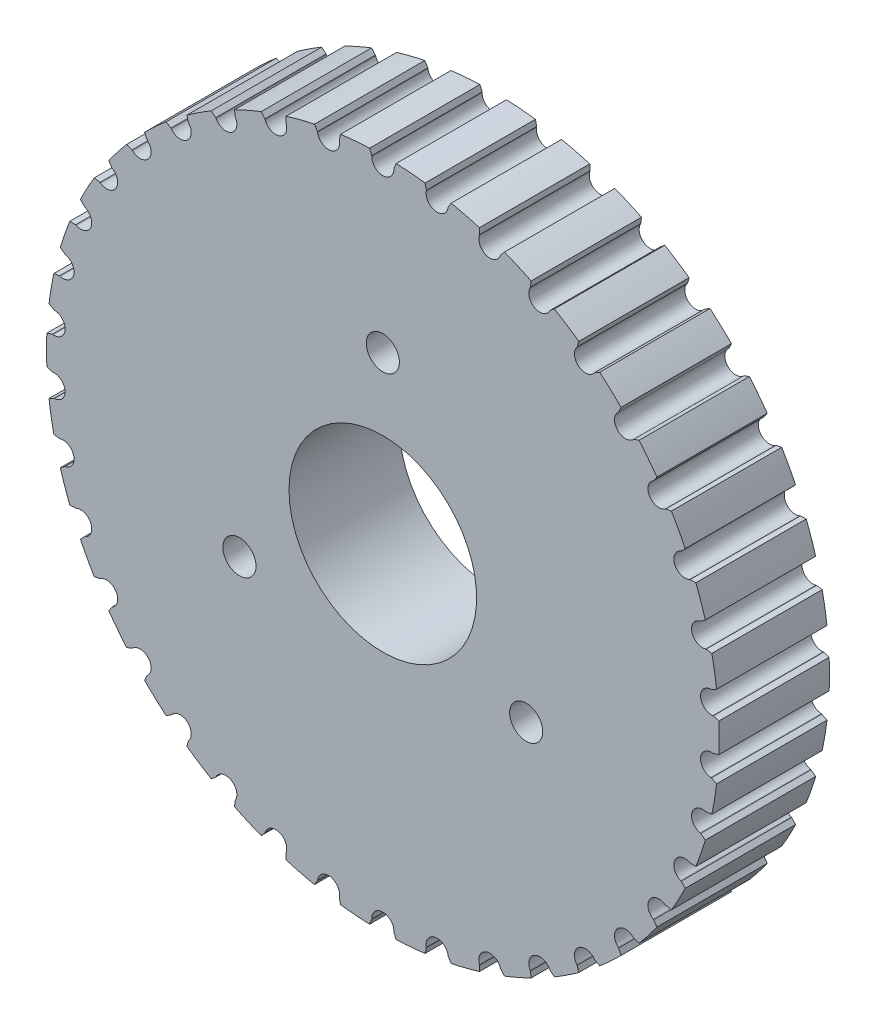
SolidWorks part; units mm, degrees
ref_plane "Спереди" through (0, 0, 0) normal (0, 0, 1) x (1, 0, 0)
ref_plane "Сверху" through (0, 0, 0) normal (0, 1, 0) x (1, 0, 0)
ref_plane "Справа" through (0, 0, 0) normal (1, 0, 0) x (0, 0, -1)
sketch "Эскиз1" plane through (0, 0, 0) normal (0, 0, 1) x (1, 0, 0)
  line L0 (0, 0) -> (0, 54.1155) construction
  line L1 (-1.2, 30.4464) -> (-1, 29.9592)
  line L2 (3.8277, 30.2286) -> (3.9448, 29.7152)
  line L3 (1, 29.9592) -> (1.2, 30.4464)
  line L4 (0, 30.47) -> (13.54, 30.47) construction
  line L5 (1, 29.9592) -> (1, 29.8903)
  line L6 (5.9175, 29.386) -> (6.1949, 29.8336)
  line L7 (-1, 29.9592) -> (-1, 29.8903)
  line L8 (5.9175, 29.386) -> (5.9061, 29.3181)
  line L9 (3.9448, 29.7152) -> (3.9334, 29.6473)
  line L10 (8.7509, 29.1863) -> (8.7819, 28.6606)
  line L11 (10.6736, 28.0112) -> (11.0209, 28.4071)
  line L12 (10.6736, 28.0112) -> (10.6512, 27.9461)
  line L13 (8.7819, 28.6606) -> (8.7596, 28.5955)
  line L14 (13.4355, 27.3479) -> (13.3795, 26.8243)
  line L15 (15.1385, 25.8724) -> (15.5462, 26.2056)
  line L16 (15.1385, 25.8724) -> (15.1057, 25.8118)
  line L17 (13.3795, 26.8243) -> (13.3468, 26.7637)
  line L18 (17.7536, 24.7635) -> (17.6122, 24.2562)
  line L19 (19.1905, 23.0278) -> (19.6475, 23.2894)
  line L20 (19.1905, 23.0278) -> (19.1482, 22.9735)
  line L21 (17.6122, 24.2562) -> (17.5699, 24.2019)
  line L22 (21.5874, 21.5036) -> (21.3644, 21.0265)
  line L23 (22.719, 19.5551) -> (23.2129, 19.7379)
  line L24 (22.719, 19.5551) -> (22.6683, 19.5085)
  line L25 (21.3644, 21.0265) -> (21.3138, 20.9799)
  line L26 (24.8323, 17.6572) -> (24.5339, 17.2233)
  line L27 (25.6278, 15.549) -> (26.145, 15.648)
  line L28 (25.6278, 15.549) -> (25.5701, 15.5113)
  line L29 (24.5339, 17.2233) -> (24.4762, 17.1856)
  line L30 (27.3999, 13.3291) -> (27.0341, 12.9502)
  line L31 (27.8375, 11.1187) -> (28.364, 11.1312)
  line L32 (27.8375, 11.1187) -> (27.7745, 11.091)
  line L33 (27.0341, 12.9502) -> (26.9711, 12.9226)
  line L34 (29.2201, 8.6374) -> (28.797, 8.3239)
  line L35 (29.2879, 6.3851) -> (29.8093, 6.3109)
  line L36 (29.2879, 6.3851) -> (29.2212, 6.3682)
  line L37 (28.797, 8.3239) -> (28.7302, 8.307)
  line L38 (30.2433, 3.7101) -> (29.7743, 3.4706)
  line L39 (29.9395, 1.4774) -> (30.4415, 1.3183)
  line L40 (29.9395, 1.4774) -> (29.8708, 1.4717)
  line L41 (29.7743, 3.4706) -> (29.7057, 3.4649)
  line L42 (30.4415, -1.3183) -> (29.9395, -1.4774)
  line L43 (29.7743, -3.4706) -> (30.2433, -3.7101)
  line L44 (29.7743, -3.4706) -> (29.7057, -3.4649)
  line L45 (29.9395, -1.4774) -> (29.8708, -1.4717)
  line L46 (29.8093, -6.3109) -> (29.2879, -6.3851)
  line L47 (28.797, -8.3239) -> (29.2201, -8.6374)
  line L48 (28.797, -8.3239) -> (28.7302, -8.307)
  line L49 (29.2879, -6.3851) -> (29.2212, -6.3682)
  line L50 (28.364, -11.1312) -> (27.8375, -11.1187)
  line L51 (27.0341, -12.9502) -> (27.3999, -13.3291)
  line L52 (27.0341, -12.9502) -> (26.9711, -12.9226)
  line L53 (27.8375, -11.1187) -> (27.7745, -11.091)
  line L54 (26.145, -15.648) -> (25.6278, -15.549)
  line L55 (24.5339, -17.2233) -> (24.8323, -17.6572)
  line L56 (24.5339, -17.2233) -> (24.4762, -17.1856)
  line L57 (25.6278, -15.549) -> (25.5701, -15.5113)
  line L58 (23.2129, -19.7379) -> (22.719, -19.5551)
  line L59 (21.3644, -21.0265) -> (21.5874, -21.5036)
  line L60 (21.3644, -21.0265) -> (21.3138, -20.9799)
  line L61 (22.719, -19.5551) -> (22.6683, -19.5085)
  line L62 (19.6475, -23.2894) -> (19.1905, -23.0278)
  line L63 (17.6122, -24.2562) -> (17.7536, -24.7635)
  line L64 (17.6122, -24.2562) -> (17.5699, -24.2019)
  line L65 (19.1905, -23.0278) -> (19.1482, -22.9735)
  line L66 (15.5462, -26.2056) -> (15.1385, -25.8724)
  line L67 (13.3795, -26.8243) -> (13.4355, -27.3479)
  line L68 (13.3795, -26.8243) -> (13.3468, -26.7637)
  line L69 (15.1385, -25.8724) -> (15.1057, -25.8118)
  line L70 (11.0209, -28.4071) -> (10.6736, -28.0112)
  line L71 (8.7819, -28.6606) -> (8.7509, -29.1863)
  line L72 (8.7819, -28.6606) -> (8.7596, -28.5955)
  line L73 (10.6736, -28.0112) -> (10.6512, -27.9461)
  line L74 (6.1949, -29.8336) -> (5.9175, -29.386)
  line L75 (3.9448, -29.7152) -> (3.8277, -30.2286)
  line L76 (3.9448, -29.7152) -> (3.9334, -29.6473)
  line L77 (5.9175, -29.386) -> (5.9061, -29.3181)
  line L78 (1.2, -30.4464) -> (1, -29.9592)
  line L79 (-1, -29.9592) -> (-1.2, -30.4464)
  line L80 (-1, -29.9592) -> (-1, -29.8903)
  line L81 (1, -29.9592) -> (1, -29.8903)
  line L82 (-3.8277, -30.2286) -> (-3.9448, -29.7152)
  line L83 (-5.9175, -29.386) -> (-6.1949, -29.8336)
  line L84 (-5.9175, -29.386) -> (-5.9061, -29.3181)
  line L85 (-3.9448, -29.7152) -> (-3.9334, -29.6473)
  line L86 (-8.7509, -29.1863) -> (-8.7819, -28.6606)
  line L87 (-10.6736, -28.0112) -> (-11.0209, -28.4071)
  line L88 (-10.6736, -28.0112) -> (-10.6512, -27.9461)
  line L89 (-8.7819, -28.6606) -> (-8.7596, -28.5955)
  line L90 (-13.4355, -27.3479) -> (-13.3795, -26.8243)
  line L91 (-15.1385, -25.8724) -> (-15.5462, -26.2056)
  line L92 (-15.1385, -25.8724) -> (-15.1057, -25.8118)
  line L93 (-13.3795, -26.8243) -> (-13.3468, -26.7637)
  line L94 (-17.7536, -24.7635) -> (-17.6122, -24.2562)
  line L95 (-19.1905, -23.0278) -> (-19.6475, -23.2894)
  line L96 (-19.1905, -23.0278) -> (-19.1482, -22.9735)
  line L97 (-17.6122, -24.2562) -> (-17.5699, -24.2019)
  line L98 (-21.5874, -21.5036) -> (-21.3644, -21.0265)
  line L99 (-22.719, -19.5551) -> (-23.2129, -19.7379)
  line L100 (-22.719, -19.5551) -> (-22.6683, -19.5085)
  line L101 (-21.3644, -21.0265) -> (-21.3138, -20.9799)
  line L102 (-24.8323, -17.6572) -> (-24.5339, -17.2233)
  line L103 (-25.6278, -15.549) -> (-26.145, -15.648)
  line L104 (-25.6278, -15.549) -> (-25.5701, -15.5113)
  line L105 (-24.5339, -17.2233) -> (-24.4762, -17.1856)
  line L106 (-27.3999, -13.3291) -> (-27.0341, -12.9502)
  line L107 (-27.8375, -11.1187) -> (-28.364, -11.1312)
  line L108 (-27.8375, -11.1187) -> (-27.7745, -11.091)
  line L109 (-27.0341, -12.9502) -> (-26.9711, -12.9226)
  line L110 (-29.2201, -8.6374) -> (-28.797, -8.3239)
  line L111 (-29.2879, -6.3851) -> (-29.8093, -6.3109)
  line L112 (-29.2879, -6.3851) -> (-29.2212, -6.3682)
  line L113 (-28.797, -8.3239) -> (-28.7302, -8.307)
  line L114 (-30.2433, -3.7101) -> (-29.7743, -3.4706)
  line L115 (-29.9395, -1.4774) -> (-30.4415, -1.3183)
  line L116 (-29.9395, -1.4774) -> (-29.8708, -1.4717)
  line L117 (-29.7743, -3.4706) -> (-29.7057, -3.4649)
  line L118 (-30.4415, 1.3183) -> (-29.9395, 1.4774)
  line L119 (-29.7743, 3.4706) -> (-30.2433, 3.7101)
  line L120 (-29.7743, 3.4706) -> (-29.7057, 3.4649)
  line L121 (-29.9395, 1.4774) -> (-29.8708, 1.4717)
  line L122 (-29.8093, 6.3109) -> (-29.2879, 6.3851)
  line L123 (-28.797, 8.3239) -> (-29.2201, 8.6374)
  line L124 (-28.797, 8.3239) -> (-28.7302, 8.307)
  line L125 (-29.2879, 6.3851) -> (-29.2212, 6.3682)
  line L126 (-28.364, 11.1312) -> (-27.8375, 11.1187)
  line L127 (-27.0341, 12.9502) -> (-27.3999, 13.3291)
  line L128 (-27.0341, 12.9502) -> (-26.9711, 12.9226)
  line L129 (-27.8375, 11.1187) -> (-27.7745, 11.091)
  line L130 (-26.145, 15.648) -> (-25.6278, 15.549)
  line L131 (-24.5339, 17.2233) -> (-24.8323, 17.6572)
  line L132 (-24.5339, 17.2233) -> (-24.4762, 17.1856)
  line L133 (-25.6278, 15.549) -> (-25.5701, 15.5113)
  line L134 (-23.2129, 19.7379) -> (-22.719, 19.5551)
  line L135 (-21.3644, 21.0265) -> (-21.5874, 21.5036)
  line L136 (-21.3644, 21.0265) -> (-21.3138, 20.9799)
  line L137 (-22.719, 19.5551) -> (-22.6683, 19.5085)
  line L138 (-19.6475, 23.2894) -> (-19.1905, 23.0278)
  line L139 (-17.6122, 24.2562) -> (-17.7536, 24.7635)
  line L140 (-17.6122, 24.2562) -> (-17.5699, 24.2019)
  line L141 (-19.1905, 23.0278) -> (-19.1482, 22.9735)
  line L142 (-15.5462, 26.2056) -> (-15.1385, 25.8724)
  line L143 (-13.3795, 26.8243) -> (-13.4355, 27.3479)
  line L144 (-13.3795, 26.8243) -> (-13.3468, 26.7637)
  line L145 (-15.1385, 25.8724) -> (-15.1057, 25.8118)
  line L146 (-11.0209, 28.4071) -> (-10.6736, 28.0112)
  line L147 (-8.7819, 28.6606) -> (-8.7509, 29.1863)
  line L148 (-8.7819, 28.6606) -> (-8.7596, 28.5955)
  line L149 (-10.6736, 28.0112) -> (-10.6512, 27.9461)
  line L150 (-6.1949, 29.8336) -> (-5.9175, 29.386)
  line L151 (-3.9448, 29.7152) -> (-3.8277, 30.2286)
  line L152 (-3.9448, 29.7152) -> (-3.9334, 29.6473)
  line L153 (-5.9175, 29.386) -> (-5.9061, 29.3181)
  arc A0 (-1.2, 30.4464) -> (-3.8277, 30.2286) centre (0, 0) ccw
  arc A1 (-1, 29.8903) -> (1, 29.8903) centre (0, 29.8903) ccw
  arc A2 (3.9334, 29.6473) -> (5.9061, 29.3181) centre (4.9198, 29.4827) ccw
  arc A3 (8.7596, 28.5955) -> (10.6512, 27.9461) centre (9.7054, 28.2708) ccw
  arc A4 (13.3468, 26.7637) -> (15.1057, 25.8118) centre (14.2262, 26.2878) ccw
  arc A5 (17.5699, 24.2019) -> (19.1482, 22.9735) centre (18.359, 23.5877) ccw
  arc A6 (21.3138, 20.9799) -> (22.6683, 19.5085) centre (21.991, 20.2442) ccw
  arc A7 (24.4762, 17.1856) -> (25.5701, 15.5113) centre (25.0232, 16.3485) ccw
  arc A8 (26.9711, 12.9226) -> (27.7745, 11.091) centre (27.3728, 12.0068) ccw
  arc A9 (28.7302, 8.307) -> (29.2212, 6.3682) centre (28.9757, 7.3376) ccw
  arc A10 (29.7057, 3.4649) -> (29.8708, 1.4717) centre (29.7883, 2.4683) ccw
  arc A11 (29.8708, -1.4717) -> (29.7057, -3.4649) centre (29.7883, -2.4683) ccw
  arc A12 (29.2212, -6.3682) -> (28.7302, -8.307) centre (28.9757, -7.3376) ccw
  arc A13 (27.7745, -11.091) -> (26.9711, -12.9226) centre (27.3728, -12.0068) ccw
  arc A14 (25.5701, -15.5113) -> (24.4762, -17.1856) centre (25.0232, -16.3485) ccw
  arc A15 (22.6683, -19.5085) -> (21.3138, -20.9799) centre (21.991, -20.2442) ccw
  arc A16 (19.1482, -22.9735) -> (17.5699, -24.2019) centre (18.359, -23.5877) ccw
  arc A17 (15.1057, -25.8118) -> (13.3468, -26.7637) centre (14.2262, -26.2878) ccw
  arc A18 (10.6512, -27.9461) -> (8.7596, -28.5955) centre (9.7054, -28.2708) ccw
  arc A19 (5.9061, -29.3181) -> (3.9334, -29.6473) centre (4.9198, -29.4827) ccw
  arc A20 (1, -29.8903) -> (-1, -29.8903) centre (0, -29.8903) ccw
  arc A21 (-3.9334, -29.6473) -> (-5.9061, -29.3181) centre (-4.9198, -29.4827) ccw
  arc A22 (-8.7596, -28.5955) -> (-10.6512, -27.9461) centre (-9.7054, -28.2708) ccw
  arc A23 (-13.3468, -26.7637) -> (-15.1057, -25.8118) centre (-14.2262, -26.2878) ccw
  arc A24 (-17.5699, -24.2019) -> (-19.1482, -22.9735) centre (-18.359, -23.5877) ccw
  arc A25 (-21.3138, -20.9799) -> (-22.6683, -19.5085) centre (-21.991, -20.2442) ccw
  arc A26 (-24.4762, -17.1856) -> (-25.5701, -15.5113) centre (-25.0232, -16.3485) ccw
  arc A27 (-26.9711, -12.9226) -> (-27.7745, -11.091) centre (-27.3728, -12.0068) ccw
  arc A28 (-28.7302, -8.307) -> (-29.2212, -6.3682) centre (-28.9757, -7.3376) ccw
  arc A29 (-29.7057, -3.4649) -> (-29.8708, -1.4717) centre (-29.7883, -2.4683) ccw
  arc A30 (-29.8708, 1.4717) -> (-29.7057, 3.4649) centre (-29.7883, 2.4683) ccw
  arc A31 (-29.2212, 6.3682) -> (-28.7302, 8.307) centre (-28.9757, 7.3376) ccw
  arc A32 (-27.7745, 11.091) -> (-26.9711, 12.9226) centre (-27.3728, 12.0068) ccw
  arc A33 (-25.5701, 15.5113) -> (-24.4762, 17.1856) centre (-25.0232, 16.3485) ccw
  arc A34 (-22.6683, 19.5085) -> (-21.3138, 20.9799) centre (-21.991, 20.2442) ccw
  arc A35 (-19.1482, 22.9735) -> (-17.5699, 24.2019) centre (-18.359, 23.5877) ccw
  arc A36 (-15.1057, 25.8118) -> (-13.3468, 26.7637) centre (-14.2262, 26.2878) ccw
  arc A37 (-10.6512, 27.9461) -> (-8.7596, 28.5955) centre (-9.7054, 28.2708) ccw
  arc A38 (-5.9061, 29.3181) -> (-3.9334, 29.6473) centre (-4.9198, 29.4827) ccw
  arc A39 (-6.1949, 29.8336) -> (-8.7509, 29.1863) centre (0, 0) ccw
  arc A40 (-11.0209, 28.4071) -> (-13.4355, 27.3479) centre (0, 0) ccw
  arc A41 (-15.5462, 26.2056) -> (-17.7536, 24.7635) centre (0, 0) ccw
  arc A42 (-19.6475, 23.2894) -> (-24.8323, 17.6572) centre (0, 0) ccw
  arc A43 (-26.145, 15.648) -> (-27.3999, 13.3291) centre (0, 0) ccw
  arc A44 (-28.364, 11.1312) -> (-29.2201, 8.6374) centre (0, 0) ccw
  arc A45 (-29.8093, 6.3109) -> (-30.2433, 3.7101) centre (0, 0) ccw
  arc A46 (-30.4415, 1.3183) -> (-30.4415, -1.3183) centre (0, 0) ccw
  arc A47 (-30.2433, -3.7101) -> (-29.8093, -6.3109) centre (0, 0) ccw
  arc A48 (-29.2201, -8.6374) -> (-28.364, -11.1312) centre (0, 0) ccw
  arc A49 (-27.3999, -13.3291) -> (-26.145, -15.648) centre (0, 0) ccw
  arc A50 (-24.8323, -17.6572) -> (-23.2129, -19.7379) centre (0, 0) ccw
  arc A51 (-21.5874, -21.5036) -> (-19.6475, -23.2894) centre (0, 0) ccw
  arc A52 (-17.7536, -24.7635) -> (-15.5462, -26.2056) centre (0, 0) ccw
  arc A53 (-13.4355, -27.3479) -> (-11.0209, -28.4071) centre (0, 0) ccw
  arc A54 (-8.7509, -29.1863) -> (-6.1949, -29.8336) centre (0, 0) ccw
  arc A55 (-3.8277, -30.2286) -> (-1.2, -30.4464) centre (0, 0) ccw
  arc A56 (1.2, -30.4464) -> (3.8277, -30.2286) centre (0, 0) ccw
  arc A57 (6.1949, -29.8336) -> (8.7509, -29.1863) centre (0, 0) ccw
  arc A58 (11.0209, -28.4071) -> (13.4355, -27.3479) centre (0, 0) ccw
  arc A59 (15.5462, -26.2056) -> (17.7536, -24.7635) centre (0, 0) ccw
  arc A60 (19.6475, -23.2894) -> (21.5874, -21.5036) centre (0, 0) ccw
  arc A61 (23.2129, -19.7379) -> (24.8323, -17.6572) centre (0, 0) ccw
  arc A62 (26.145, -15.648) -> (27.3999, -13.3291) centre (0, 0) ccw
  arc A63 (28.364, -11.1312) -> (29.2201, -8.6374) centre (0, 0) ccw
  arc A64 (29.8093, -6.3109) -> (30.2433, -3.7101) centre (0, 0) ccw
  arc A65 (30.4415, -1.3183) -> (30.4415, 1.3183) centre (0, 0) ccw
  arc A66 (30.2433, 3.7101) -> (29.8093, 6.3109) centre (0, 0) ccw
  arc A67 (29.2201, 8.6374) -> (28.364, 11.1312) centre (0, 0) ccw
  arc A68 (27.3999, 13.3291) -> (26.145, 15.648) centre (0, 0) ccw
  arc A69 (24.8323, 17.6572) -> (23.2129, 19.7379) centre (0, 0) ccw
  arc A70 (21.5874, 21.5036) -> (19.6475, 23.2894) centre (0, 0) ccw
  arc A71 (17.7536, 24.7635) -> (15.5462, 26.2056) centre (0, 0) ccw
  arc A72 (13.4355, 27.3479) -> (11.0209, 28.4071) centre (0, 0) ccw
  arc A73 (8.7509, 29.1863) -> (6.1949, 29.8336) centre (0, 0) ccw
  arc A74 (3.8277, 30.2286) -> (1.2, 30.4464) centre (0, 0) ccw
  circle A75 centre (0, 0) radius 8.5
  circle A76 centre (0, 15) radius 1.5
  circle A77 centre (12.9904, -7.5) radius 1.5
  circle A78 centre (-12.9904, -7.5) radius 1.5
  dimension "D1" = 60.94
  dimension "D2" = 15
  dimension "D4" = 1.2
  dimension "D5" = 2.4
  dimension "D8" = 1
extrude "Вытянуть1" add sketch "Эскиз1" along normal blind 10
